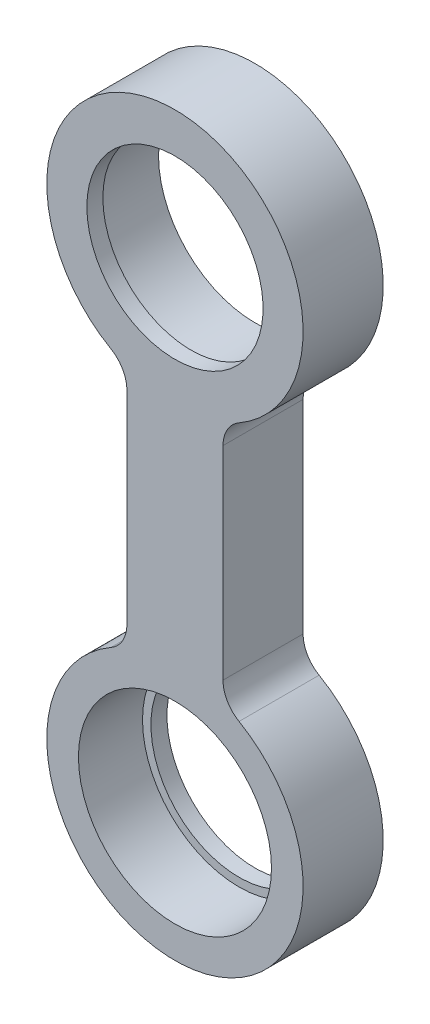
SolidWorks part; units mm, degrees
ref_plane "前视基准面" through (0, 0, 0) normal (0, 0, 1) x (1, 0, 0)
ref_plane "上视基准面" through (0, 0, 0) normal (0, 1, 0) x (1, 0, 0)
ref_plane "右视基准面" through (0, 0, 0) normal (1, 0, 0) x (0, 0, -1)
ref_plane "基准面1" through (0, 0, 0) normal (0, 0, -1) x (-1, 0, 0)
sketch "草图1" plane through (0, 0, 0) normal (0, 0, -1) x (-1, 0, 0)
  line L0 (-3, 22.5838) -> (-3, 7.4162)
  line L1 (3, 7.4162) -> (3, 22.5838)
  arc A0 (3, 22.5838) -> (-3, 22.5838) centre (0, 30) ccw
  arc A1 (-3, 7.4162) -> (3, 7.4162) centre (0, 0) ccw
extrude "凸台-拉伸1" add sketch "草图1" against normal blind 5
hole_wizard "M10 六角头螺栓的柱形沉头孔1" positions "草图3" profile "草图2" counterbore size "M10" standard "ANSI Metric"
sketch "草图3" plane through (0, 0, 0) normal (0, 0, -1) x (-1, 0, 0)
  point P0 (0, 30)
sketch "草图2" plane through (0, 30, 0) normal (1, 0, 0) x (0, 1, 0)
  line L0 (0, 0) -> (0, 5)
  line L1 (0, 5) -> (5.5, 5)
  line L3 (5.5, 5) -> (5.5, 4)
  line L4 (5.5, 4) -> (6.025, 4)
  line L5 (6.025, 4) -> (6.025, 0)
  line L7 (6.025, 0) -> (0, 0)
  line L11 (0, -6.35) -> (0, 107.95) construction
  dimension "通孔孔直径" = 11
  dimension "通孔孔深度" = 5
  dimension "柱形沉头孔直径" = 12.05
  dimension "柱形沉头孔深度" = 4
hole_wizard "M10 六角头螺栓的柱形沉头孔2" positions "草图5" profile "草图4" counterbore size "M10" standard "ANSI Metric"
sketch "草图5" plane through (0, 0, 5) normal (0, 0, 1) x (1, 0, 0)
  point P0 (0, 0)
sketch "草图4" plane through (0, 0, 5) normal (1, 0, 0) x (0, -1, 0)
  line L0 (0, 0) -> (0, 5)
  line L1 (0, 5) -> (5.5, 5)
  line L3 (5.5, 5) -> (5.5, 4)
  line L4 (5.5, 4) -> (6.025, 4)
  line L5 (6.025, 4) -> (6.025, 0)
  line L7 (6.025, 0) -> (0, 0)
  line L11 (0, -6.35) -> (0, 107.95) construction
  dimension "通孔孔直径" = 11
  dimension "通孔孔深度" = 5
  dimension "柱形沉头孔直径" = 12.05
  dimension "柱形沉头孔深度" = 4
fillet "圆角1" radius 2 4 edges at (-3, 22.5838, 2.5) (3, 22.5838, 2.5) (-3, 7.4162, 2.5) (3, 7.4162, 2.5)
